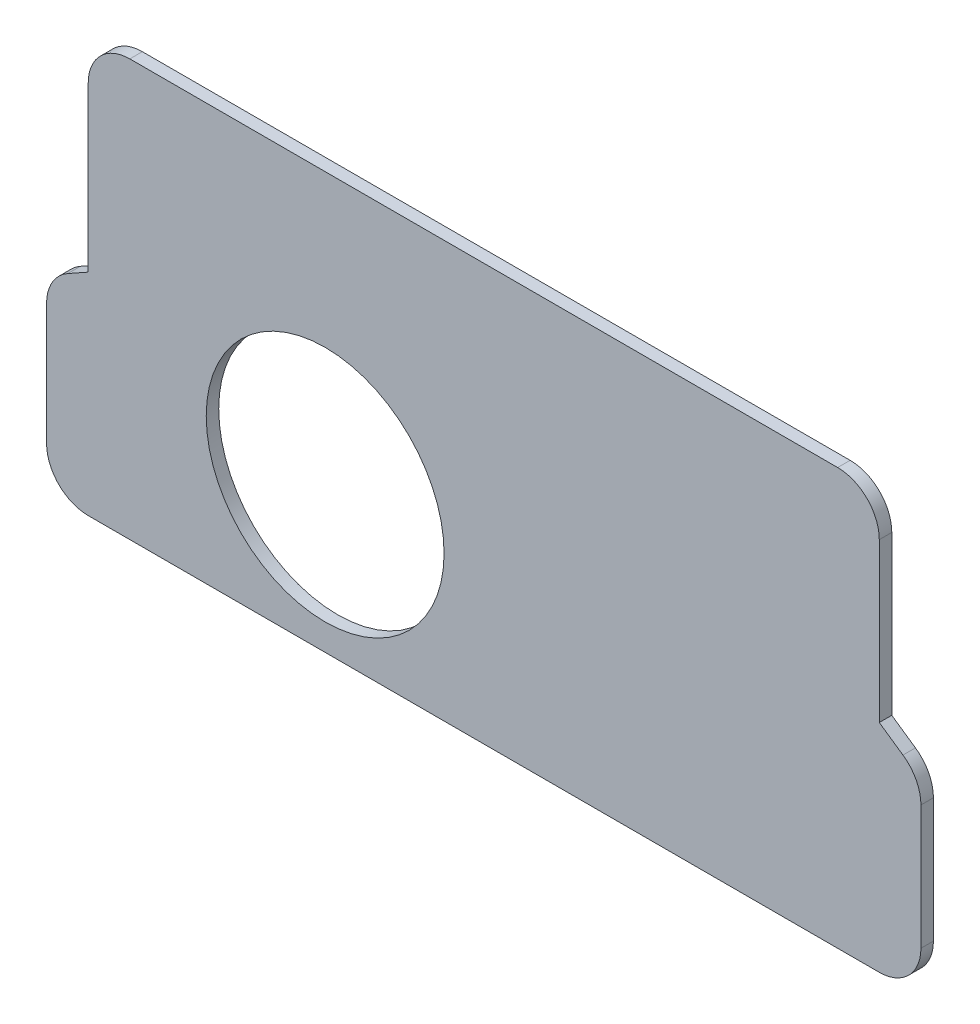
SolidWorks part; units mm, degrees
material "Thornel Mat VMA"
ref_plane "前视基准面" through (0, 0, 0) normal (0, 0, 1) x (1, 0, 0)
ref_plane "上视基准面" through (0, 0, 0) normal (0, 1, 0) x (1, 0, 0)
ref_plane "右视基准面" through (0, 0, 0) normal (1, 0, 0) x (0, 0, -1)
other "Configuration Table"
sketch "草图1" plane through (0, 0, 0) normal (0, 0, 1) x (1, 0, 0)
  line L0 (0, 10) -> (0, 39.1866)
  line L1 (5.1248, 47.9177) -> (10, 50.6399)
  line L2 (10, 50.6399) -> (10, 90)
  line L3 (20, 100) -> (190, 100)
  line L4 (200, 90) -> (200, 51.9634)
  line L5 (200, 51.9634) -> (205.6833, 48.0378)
  line L6 (210, 39.8098) -> (210, 10)
  line L7 (200, 0) -> (10, 0)
  line L9 (16.6077, 94.9776) -> (119.8077, 94.9776) construction
  line L10 (16.6077, 94.9776) -> (16.6077, 4.2776) construction
  line L11 (16.6077, 4.2776) -> (119.8077, 4.2776) construction
  line L12 (119.8077, 94.9776) -> (119.8077, 4.2776) construction
  line L13 (126.7178, 83.3205) -> (183.2178, 83.3205) construction
  line L14 (126.7178, 83.3205) -> (126.7178, 11.8205) construction
  line L15 (126.7178, 11.8205) -> (183.2178, 11.8205) construction
  line L16 (183.2178, 83.3205) -> (183.2178, 11.8205) construction
  arc A0 (210, 10) -> (200, 0) centre (200, 10) cw
  arc A1 (0, 10) -> (10, 0) centre (10, 10) ccw
  arc A2 (205.6833, 48.0378) -> (210, 39.8098) centre (200, 39.8098) cw
  arc A3 (0, 39.1866) -> (5.1248, 47.9177) centre (10, 39.1866) cw
  arc A4 (190, 100) -> (200, 90) centre (190, 90) cw
  arc A5 (10, 90) -> (20, 100) centre (20, 90) cw
  circle A6 centre (66.9066, 34.8906) radius 28.5632
  point P13 (0, 0)
  dimension "D1" = 10
  dimension "D2" = 190
  dimension "D3" = 100
  dimension "D4" = 103.2
  dimension "D5" = 90.7
  dimension "D6" = 71.5
  dimension "D7" = 56.5
  dimension "D8" = 10
  dimension "D9" = 10
extrude "凸台-拉伸1" add sketch "草图1" along normal blind 3
